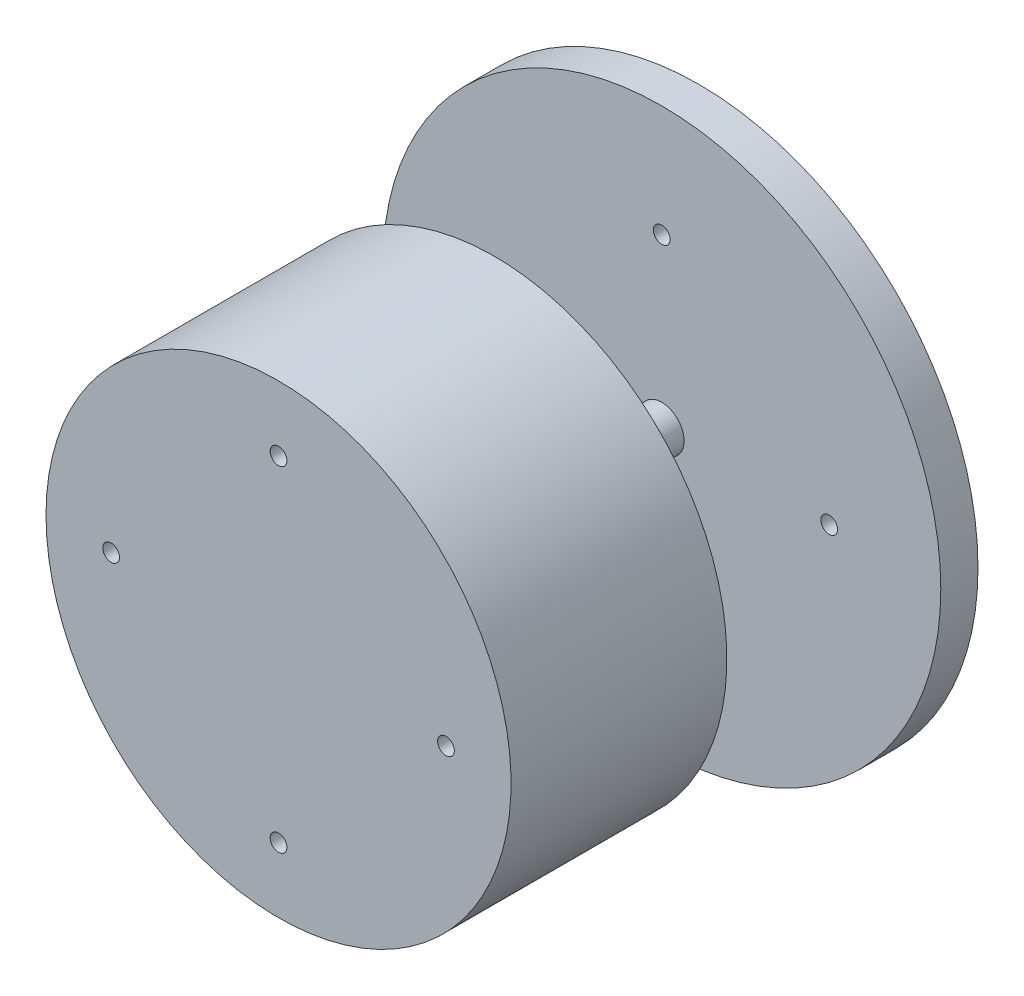
SolidWorks part; units mm, degrees
ref_plane "Front Plane" through (0, 0, 0) normal (0, 0, 1) x (1, 0, 0)
ref_plane "Top Plane" through (0, 0, 0) normal (0, 1, 0) x (1, 0, 0)
ref_plane "Right Plane" through (0, 0, 0) normal (1, 0, 0) x (0, 0, -1)
ref_plane "Plane1" through (0, 0, 55) normal (0, 0, 1) x (1, 0, 0)
sketch "Sketch1" plane through (0, 0, 55) normal (0, 0, 1) x (1, 0, 0)
  circle A0 centre (300, 300) radius 62.5
extrude "Boss-Extrude1" add sketch "Sketch1" along normal blind 58
sketch "Sketch2" plane through (0, 0, 0) normal (0, 0, 1) x (1, 0, 0)
  circle A0 centre (300, 300) radius 6
extrude "Boss-Extrude2" add sketch "Sketch2" along normal blind 113
sketch "Sketch3" plane through (0, 0, 0) normal (0, 0, 1) x (1, 0, 0)
  circle A0 centre (300, 300) radius 75
extrude "Boss-Extrude3" add sketch "Sketch3" along normal blind 10
sketch "Sketch4" plane through (0, 0, 113) normal (0, 0, 1) x (1, 0, 0)
  circle A0 centre (345, 300) radius 2.25
extrude "Cut-Extrude1" cut sketch "Sketch4" against normal blind 133
sketch "Sketch5" plane through (0, 0, 113) normal (0, 0, 1) x (1, 0, 0)
  circle A0 centre (255, 300) radius 2.25
extrude "Cut-Extrude2" cut sketch "Sketch5" against normal blind 133
sketch "Sketch6" plane through (0, 0, 113) normal (0, 0, 1) x (1, 0, 0)
  circle A0 centre (300, 345) radius 2.25
extrude "Cut-Extrude3" cut sketch "Sketch6" against normal blind 133
sketch "Sketch7" plane through (0, 0, 113) normal (0, 0, 1) x (1, 0, 0)
  circle A0 centre (300, 255) radius 2.25
extrude "Cut-Extrude4" cut sketch "Sketch7" against normal blind 133
